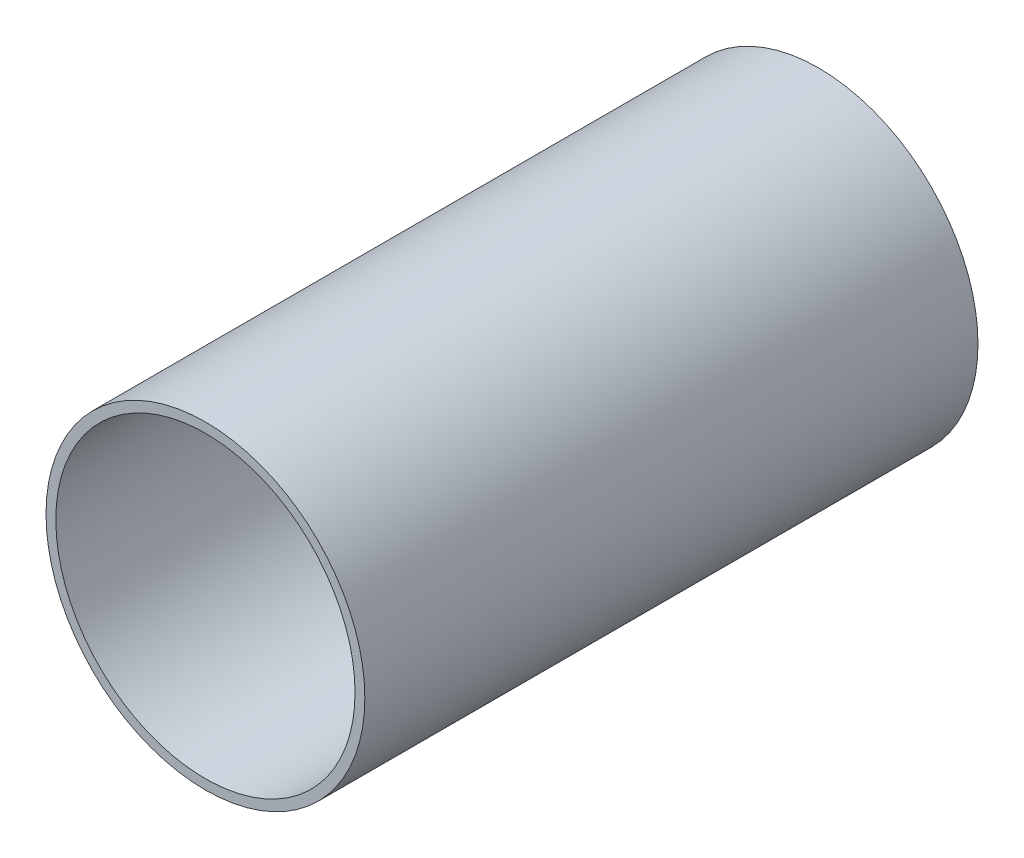
SolidWorks part; units mm, degrees
ref_plane "Front Plane" through (0, 0, 0) normal (0, 0, 1) x (1, 0, 0)
ref_plane "Top Plane" through (0, 0, 0) normal (0, 1, 0) x (1, 0, 0)
ref_plane "Right Plane" through (0, 0, 0) normal (1, 0, 0) x (0, 0, -1)
sketch "Sketch1" plane through (0, 0, 0) normal (0, 0, 1) x (1, 0, 0)
  circle A0 centre (0, 0) radius 65
  circle A1 centre (0, 0) radius 61
  dimension "D1" = 130
  dimension "D2" = 122
extrude "Boss-Extrude1" add sketch "Sketch1" along normal blind 250
